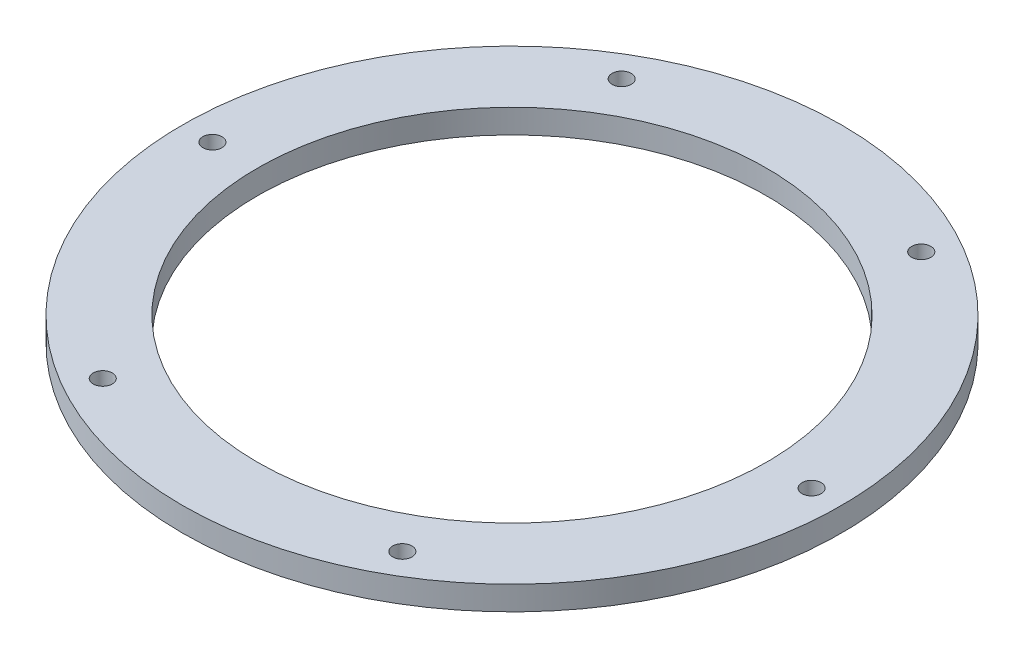
SolidWorks part; units mm, degrees
ref_plane "前视基准面" through (0, 0, 0) normal (0, 0, 1) x (1, 0, 0)
ref_plane "上视基准面" through (0, 0, 0) normal (0, 1, 0) x (1, 0, 0)
ref_plane "右视基准面" through (0, 0, 0) normal (1, 0, 0) x (0, 0, -1)
sketch "草图1" plane through (0, 0, 0) normal (0, 1, 0) x (1, 0, 0)
  circle A6 centre (0, 0) radius 50 construction
  circle A7 centre (25, 43.3013) radius 1.6
  circle A8 centre (50, 0) radius 1.6
  circle A9 centre (25, -43.3013) radius 1.6
  circle A10 centre (-25, -43.3013) radius 1.6
  circle A11 centre (-50, 0) radius 1.6
  circle A12 centre (-25, 43.3013) radius 1.6
  circle A13 centre (0, 0) radius 55
  circle A20 centre (0, 0) radius 42.5
  point P3 (23.7486, 44)
  point P4 (0, 0)
  point P5 (49.9956, 0.6628)
  point P6 (0, 0)
  point P7 (25.6218, 42.9362)
  point P9 (-25, -43.3013)
  dimension "D2" = 85
  dimension "D7" = 6
  dimension "D8" = 3.2
  dimension "D9" = 50
  dimension "D10" = 110
extrude "凸台-拉伸1" add sketch "草图1" along normal blind 4
